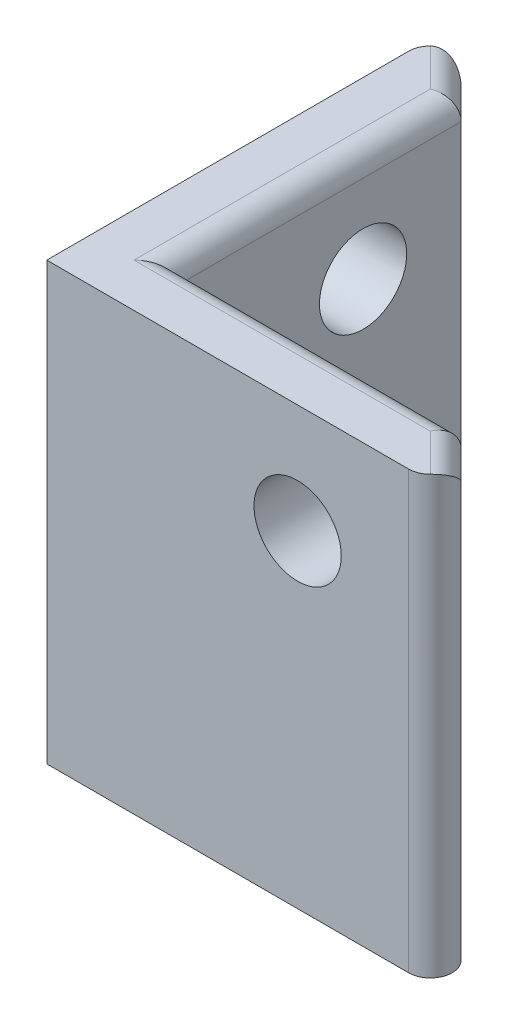
SolidWorks part; units mm, degrees
ref_plane "前视" through (0, 0, 0) normal (0, 0, 1) x (1, 0, 0)
ref_plane "上视" through (0, 0, 0) normal (0, 1, 0) x (1, 0, 0)
ref_plane "右视" through (0, 0, 0) normal (1, 0, 0) x (0, 0, -1)
sketch "Sketch1" plane through (0, 0, 0) normal (0, 1, 0) x (1, 0, 0)
  line L0 (0, 0) -> (0, 19)
  line L1 (0, 0) -> (19, 0)
  line L2 (19, 0) -> (0, 19)
  dimension "D1" = 19
  dimension "D2" = 19
extrude "Boss-Extrude1" add sketch "Sketch1" along normal blind 5
sketch "Sketch2" plane through (0, 5, 0) normal (0, 1, 0) x (1, 0, 0)
  line L0 (0, 19) -> (0, 0)
  line L1 (0, 0) -> (19, 0)
  line L2 (19, 0) -> (16, 3)
  line L3 (19, 0) -> (0, 19) construction
  line L4 (16, 3) -> (3, 3)
  line L5 (3, 3) -> (3, 16)
  line L6 (3, 16) -> (0, 19)
  dimension "D1" = 3
  dimension "D2" = 3
extrude "Boss-Extrude2" add sketch "Sketch2" along normal blind 15
sketch "Sketch3" plane through (0, 0, 0) normal (0, 0, 1) x (1, 0, 0)
  line L0 (0, 20) -> (0, 0) construction
  line L1 (0, 0) -> (19, 0) construction
  circle A0 centre (11.5, 15) radius 2
  dimension "D1" = 11.5
  dimension "D2" = 15
extrude "Cut-Extrude1" cut sketch "Sketch3" against normal through all
sketch "Sketch4" plane through (0, 0, 0) normal (-1, 0, 0) x (0, 0, 1)
  line L0 (-19, 0) -> (0, 0) construction
  line L1 (0, 20) -> (0, 0) construction
  circle A0 centre (-11.5, 15) radius 2
  dimension "D1" = 15
  dimension "D2" = 11.5
extrude "Cut-Extrude2" cut sketch "Sketch4" against normal through all
fillet "Fillet1" radius 1 6 edges at (9.5, 20, -3) (3, 20, -9.5) (1.5, 20, -17.5) (17.5, 20, -1.5) (19, 10, 0) (0, 10, -19)
